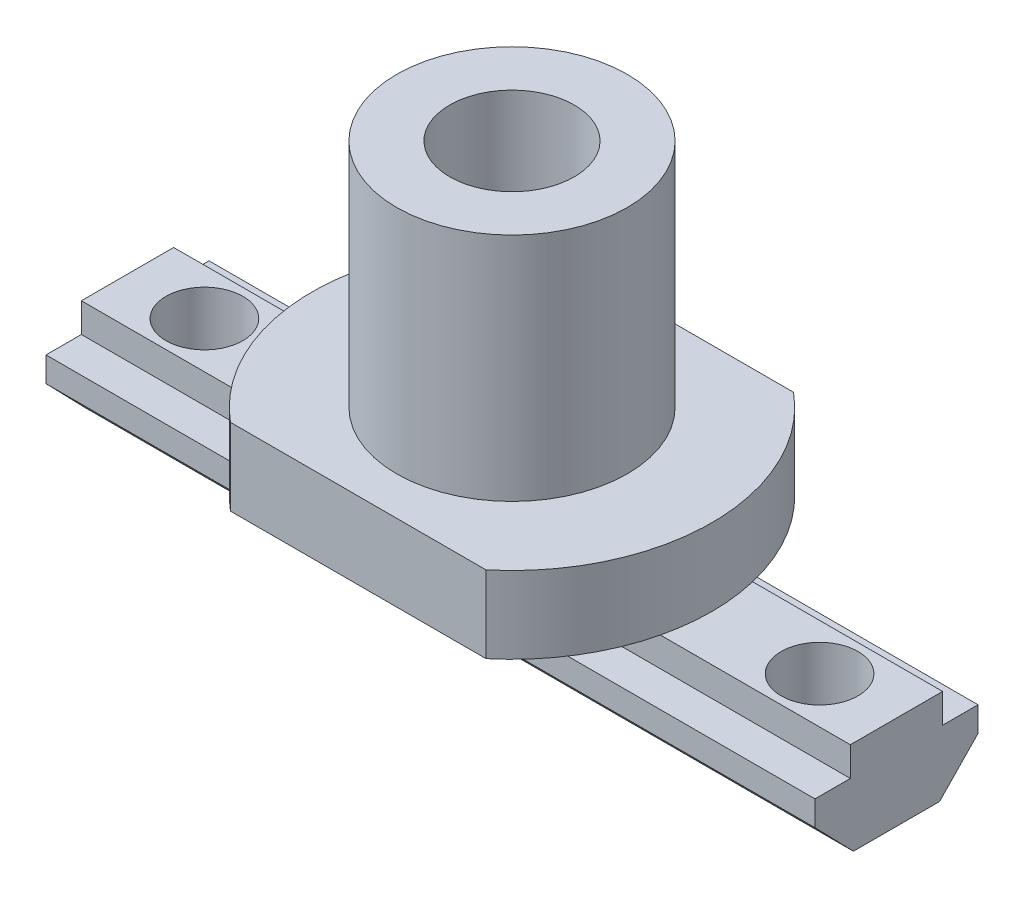
SolidWorks part; units mm, degrees
ref_plane "Front (XY)" through (0, 0, 0) normal (0, 0, 1) x (1, 0, 0)
ref_plane "Top (XZ)" through (0, 0, 0) normal (0, 1, 0) x (1, 0, 0)
ref_plane "Right (YZ)" through (0, 0, 0) normal (1, 0, 0) x (0, 0, -1)
sketch "Sketch2" plane through (0, 0, 0) normal (1, 0, 0) x (0, 0, -1)
  line L0 (0, 0) -> (0, 6.1) construction
  line L1 (-3, 6.1) -> (3, 6.1)
  line L2 (-3, 6.1) -> (-3, 4.2)
  line L3 (3, 6.1) -> (3, 4.2)
  line L4 (-3, 4.2) -> (-5.3, 4.2)
  line L5 (3, 4.2) -> (5.3, 4.2)
  line L6 (-5.3, 4.2) -> (-5.3, 2.58)
  line L7 (5.3, 4.2) -> (5.3, 2.58)
  line L8 (-2.8, 0) -> (2.8, 0)
  line L9 (-2.8, 0) -> (-5.3, 2.58)
  line L10 (2.8, 0) -> (5.3, 2.58)
  point P4 (0, 6.1)
  point P13 (0, 0)
  dimension "D1" = 6
  dimension "D2" = 1.9
  dimension "D3" = 2.3
  dimension "D4" = 1.62
  dimension "D5" = 6.1
  dimension "D6" = 5.6
extrude "Boss-Extrude1" add sketch "Sketch2" along normal mid plane 50
sketch "Sketch3" plane through (0, 6.1, 0) normal (0, 1, 0) x (1, 0, 0)
  line L0 (-20, 10) -> (-20, -10)
  line L1 (20, 10) -> (20, -10)
  line L2 (-20, 10) -> (20, 10)
  line L3 (20, -10) -> (-20, -10)
  point P4 (20, 0)
  point P6 (-20, 0)
  dimension "D1" = 20
  dimension "D2" = 20
  dimension "D3" = 20
sketch "Sketch5" plane through (0, 6.1, 0) normal (0, 1, 0) x (1, 0, 0)
  line L0 (20, -10) -> (-20, -10) construction
  line L1 (-20, 10) -> (20, 10) construction
  line L2 (8.3066, -10) -> (-8.3066, -10)
  line L3 (-8.3066, 10) -> (8.3066, 10)
  arc A0 (-8.3066, 10) -> (-8.3066, -10) centre (0, 0) ccw
  arc A1 (8.3066, -10) -> (8.3066, 10) centre (0, 0) ccw
  dimension "D1" = 26
extrude "Boss-Extrude3" add sketch "Sketch5" along normal blind 5
sketch "Sketch6" plane through (0, 11.1, 0) normal (0, 1, 0) x (1, 0, 0)
  circle A0 centre (0, 0) radius 7.5
  dimension "D1" = 15
extrude "Boss-Extrude4" add sketch "Sketch6" along normal blind 15
sketch "Sketch7" plane through (0, 26.1, 0) normal (0, 1, 0) x (1, 0, 0)
  circle A0 centre (0, 0) radius 4.05
  dimension "D1" = 8.1
extrude "Cut-Extrude1" cut sketch "Sketch7" against normal up to surface (20 mm away) up to face at (18.9123, 6.1, 0)
sketch "Sketch8" plane through (0, 6.1, 0) normal (0, 1, 0) x (1, 0, 0)
  circle A0 centre (20, 0) radius 2.5
  circle A1 centre (-20, 0) radius 2.5
  point P4 (0, 0)
  dimension "D1" = 5
  dimension "D2" = 20
  dimension "D3" = 20
extrude "Cut-Extrude2" cut sketch "Sketch8" against normal through all
